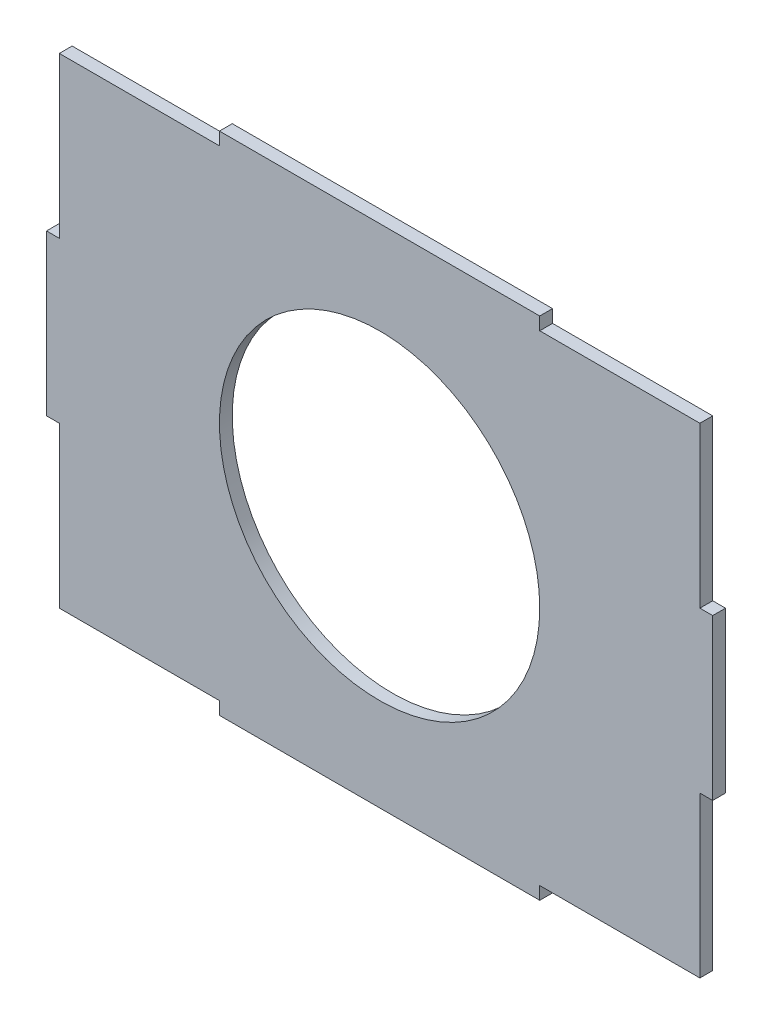
SolidWorks part; units mm, degrees
ref_plane "Front Plane" through (0, 0, 0) normal (0, 0, 1) x (1, 0, 0)
ref_plane "Top Plane" through (0, 0, 0) normal (0, 1, 0) x (1, 0, 0)
ref_plane "Right Plane" through (0, 0, 0) normal (1, 0, 0) x (0, 0, -1)
sketch "Sketch1" plane through (0, 0, 0) normal (0, 0, 1) x (1, 0, 0)
  line L0 (0, 0) -> (100, 0)
  line L1 (100, 0) -> (100, 4)
  line L2 (100, 4) -> (150, 4)
  line L3 (150, 4) -> (150, 54)
  line L4 (150, 54) -> (154, 54)
  line L5 (154, 54) -> (154, 104)
  line L6 (154, 104) -> (150, 104)
  line L7 (150, 104) -> (150, 154)
  line L8 (150, 154) -> (100, 154)
  line L9 (100, 154) -> (100, 158)
  line L10 (100, 158) -> (0, 158)
  line L11 (0, 158) -> (0, 154)
  line L12 (0, 154) -> (-50, 154)
  line L13 (-50, 154) -> (-50, 104)
  line L14 (-50, 104) -> (-54, 104)
  line L15 (-54, 104) -> (-54, 54)
  line L16 (-54, 54) -> (-50, 54)
  line L17 (-50, 54) -> (-50, 4)
  line L18 (-50, 4) -> (0, 4)
  line L19 (0, 4) -> (0, 0)
  circle A0 centre (50, 79) radius 50
  point P18 (-54, 79)
  dimension "D4" = 158
  dimension "D1" = 100
  dimension "D2" = 200
  dimension "D3" = 208
  dimension "D5" = 79
  dimension "D6" = 104
extrude "Boss-Extrude1" add sketch "Sketch1" along normal blind 4
